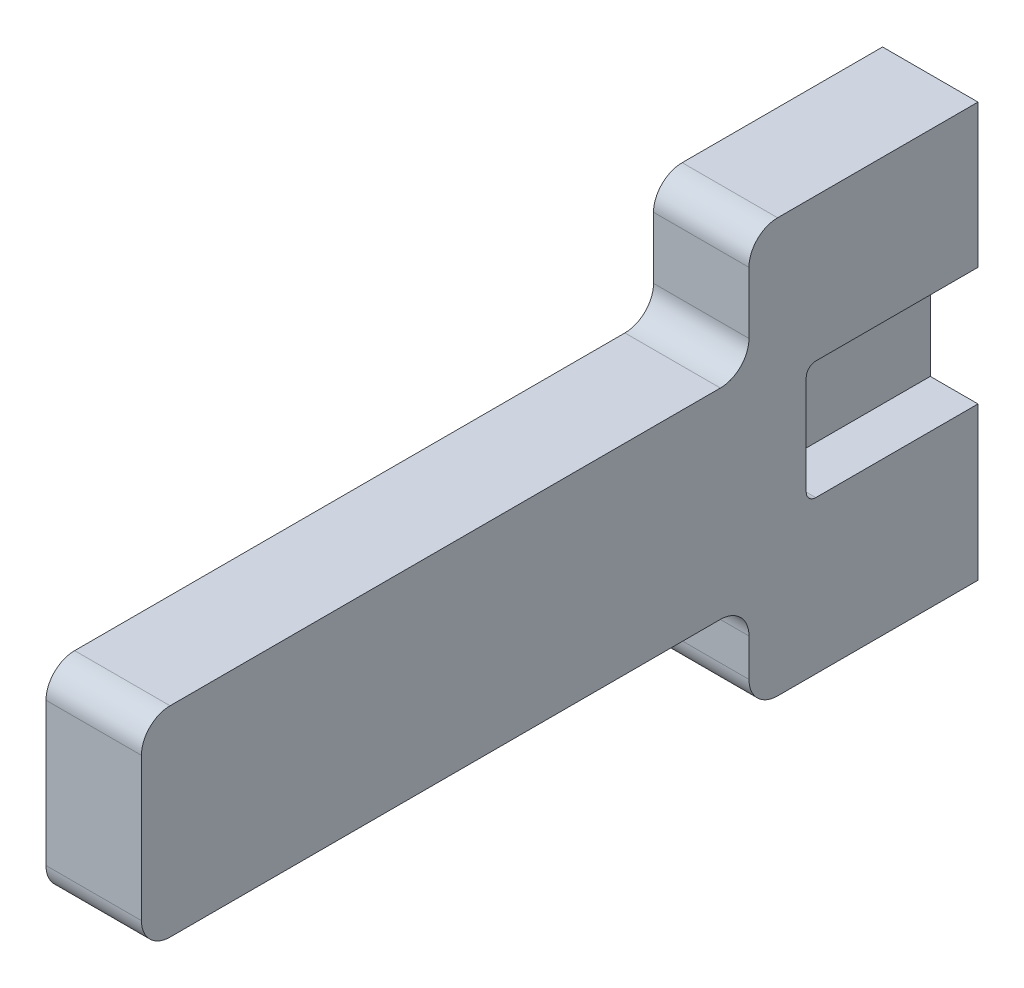
SolidWorks part; units mm, degrees
ref_plane "Alzado" through (0, 0, 0) normal (0, 0, 1) x (1, 0, 0)
ref_plane "Planta" through (0, 0, 0) normal (0, 1, 0) x (1, 0, 0)
ref_plane "Vista lateral" through (0, 0, 0) normal (1, 0, 0) x (0, 0, -1)
sketch "Croquis1" plane through (0, 0, 0) normal (1, 0, 0) x (0, 0, -1)
  line L0 (0, -10.2165) -> (0, 27.3947)
  line L1 (0, 27.3947) -> (-24, 27.3947)
  line L2 (-24, 27.3947) -> (-24, 14.9424)
  line L3 (-24, 14.9424) -> (-87.6638, 14.9424)
  line L4 (-87.6638, 14.9424) -> (-87.6638, -6.0576)
  line L5 (-87.6638, -6.0576) -> (-24, -6.0576)
  line L6 (-24, -6.0576) -> (-24, -16.0028)
  line L7 (-24, -16.0028) -> (0, -16.0028)
  line L8 (0, -16.0028) -> (0, -10.2165)
  dimension "D1" = 24
  dimension "D2" = 24
  dimension "D3" = 21
extrude "Saliente-Extruir1" add sketch "Croquis1" along normal blind 10
sketch "Croquis2" plane through (10, 0, 0) normal (1, 0, 0) x (0, 0, -1)
  line L0 (0, 0) -> (-18, 0)
  line L1 (-18, 0) -> (-18, 12.3947)
  line L2 (-18, 12.3947) -> (0, 12.3947)
  line L3 (0, -16.0028) -> (0, 27.3947) construction
  line L4 (0, 12.3947) -> (0, 0)
  line L5 (0, 27.3947) -> (-24, 27.3947) construction
  dimension "D1" = 15
  dimension "D2" = 18
extrude "Cortar-Extruir1" cut sketch "Croquis2" against normal blind 5
fillet "Redondeo1" radius 3 2 edges at (5, -6.0576, 24) (5, 14.9424, 24)
fillet "Redondeo2" radius 3 4 edges at (5, -16.0028, 24) (5, 27.3947, 24) (5, -6.0576, 87.6638) (5, 14.9424, 87.6638)
fillet "Redondeo3" radius 1 2 edges at (7.5, 0, 18) (7.5, 12.3947, 18)
